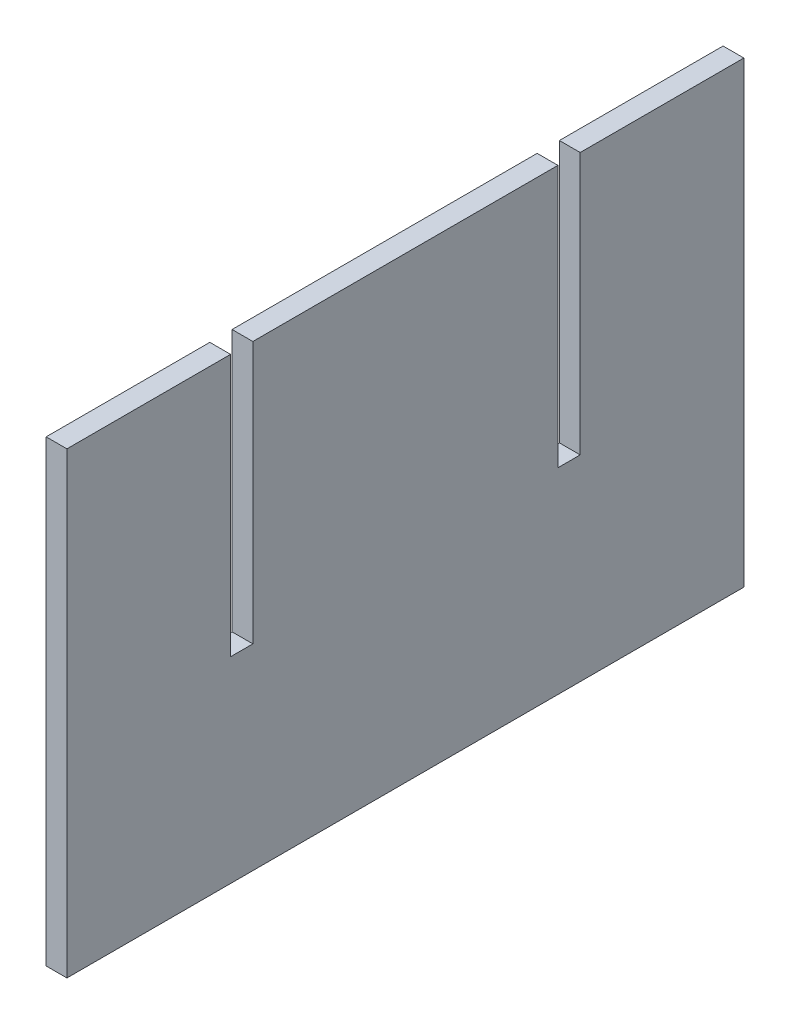
SolidWorks part; units mm, degrees
ref_plane "Front Plane" through (0, 0, 0) normal (0, 0, 1) x (1, 0, 0)
ref_plane "Top Plane" through (0, 0, 0) normal (0, 1, 0) x (1, 0, 0)
ref_plane "Right Plane" through (0, 0, 0) normal (1, 0, 0) x (0, 0, -1)
sketch "Sketch1" plane through (0, 0, 0) normal (1, 0, 0) x (0, 0, -1)
  line L0 (0, 0) -> (0, 70)
  line L1 (0, 70) -> (25, 70)
  line L2 (25, 70) -> (25, 30)
  line L3 (25, 30) -> (28.4, 30)
  line L4 (28.4, 30) -> (28.4, 70)
  line L5 (28.4, 70) -> (75, 70)
  line L6 (75, 70) -> (75, 30)
  line L7 (75, 30) -> (78.4, 30)
  line L8 (78.4, 30) -> (78.4, 70)
  line L9 (78.4, 70) -> (103.4, 70)
  line L10 (103.4, 70) -> (103.4, 0)
  line L11 (103.4, 0) -> (0, 0)
  line L12 (28.4, 30) -> (75, 30) construction
  line L13 (25, 70) -> (28.4, 70) construction
  line L14 (75, 70) -> (78.4, 70) construction
  dimension "D1" = 25
  dimension "D2" = 3.4
  dimension "D3" = 40
  dimension "D4" = 50
  dimension "D5" = 70
extrude "Boss-Extrude1" add sketch "Sketch1" along normal blind 3.175
